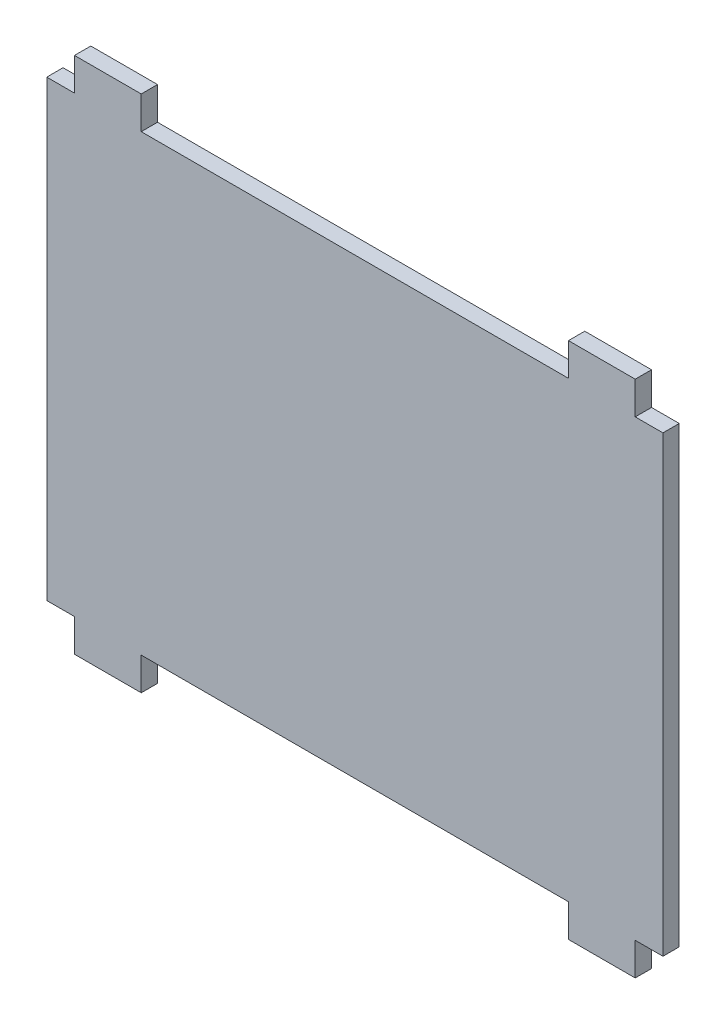
SolidWorks part; units mm, degrees
ref_plane "Front Plane" through (0, 0, 0) normal (0, 0, 1) x (1, 0, 0)
ref_plane "Top Plane" through (0, 0, 0) normal (0, 1, 0) x (1, 0, 0)
ref_plane "Right Plane" through (0, 0, 0) normal (1, 0, 0) x (0, 0, -1)
sketch "Sketch1" plane through (0, 0, 0) normal (0, 0, 1) x (1, 0, 0)
  line L0 (0.8731, 0) -> (-0.8731, 0) construction
  line L1 (-30, 0) -> (30, 0)
  line L2 (-30, 0) -> (-30, 25.25)
  line L3 (-30, 25.25) -> (30, 25.25)
  line L4 (30, 0) -> (30, 25.25)
  line L5 (0, -0.8731) -> (0, 0.8731) construction
  point P6 (0, 25.25)
  dimension "D1" = 60
  dimension "D2" = 25.25
extrude "Boss-Extrude1" add sketch "Sketch1" along normal blind 1.5875
sketch "Sketch2" plane through (0, 0, 1.5875) normal (0, 0, 1) x (1, 0, 0)
  line L0 (30, 25.25) -> (-30, 25.25) construction
  line L1 (-3.3, 25.25) -> (3.3, 25.25) construction
  line L5 (0, -0.8731) -> (0, 0.8731) construction
  line L22 (-20.8, 25.25) -> (20.8, 25.25)
  line L27 (-20.8, 25.25) -> (-20.8, 22.07)
  line L28 (-20.8, 22.07) -> (20.8, 22.07)
  line L29 (20.8, 25.25) -> (20.8, 22.07)
  line L30 (27.3, 25.25) -> (32.7, 25.25)
  line L31 (27.3, 25.25) -> (27.3, 22.07)
  line L32 (27.3, 22.07) -> (32.7, 22.07)
  line L33 (32.7, 25.25) -> (32.7, 22.07)
  line L42 (-32.7, 25.25) -> (-27.3, 25.25)
  line L43 (-32.7, 25.25) -> (-32.7, 22.07)
  line L44 (-32.7, 22.07) -> (-27.3, 22.07)
  line L45 (-27.3, 25.25) -> (-27.3, 22.07)
  line L46 (-27.3, 23.66) -> (-20.7, 23.66) construction
  line L47 (-24, 23.66) -> (-24, 25.25) construction
  line L48 (20.8, 23.66) -> (27.2, 23.66) construction
  line L49 (27.2, 23.66) -> (24, 23.66) construction
  line L50 (24, 23.66) -> (24, 25.25) construction
  point P6 (0, 25.25)
  dimension "D1" = 24
  dimension "D2" = 3.18
  dimension "D3" = 6.5
  dimension "D4" = 6.5
  dimension "D5" = 3.18
  dimension "D6" = 3.18
  dimension "D7" = 24
extrude "Cut-Extrude1" cut sketch "Sketch2" against normal blind 1.5875
mirror "Mirror1" about plane through (0, 0, 0) normal (0, 1, 0) of "Cut-Extrude1", "Boss-Extrude1"
